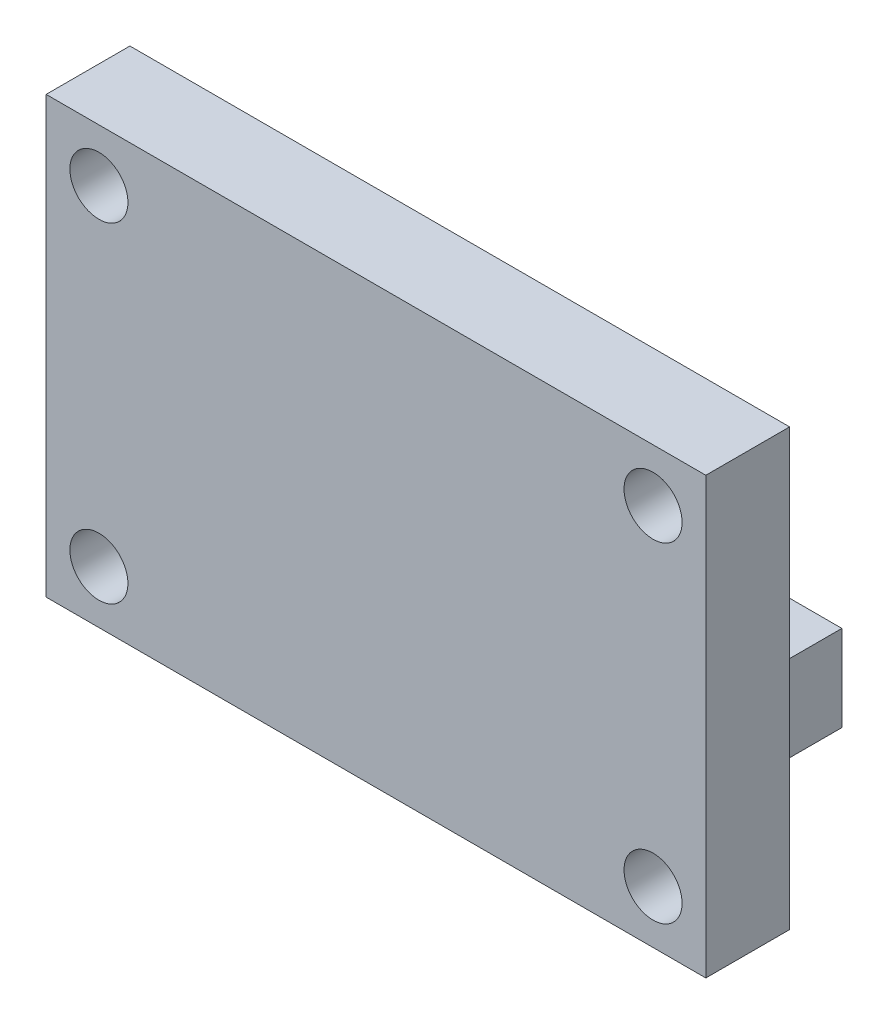
SolidWorks part; units mm, degrees
ref_plane "Front Plane" through (0, 0, 0) normal (0, 0, 1) x (1, 0, 0)
ref_plane "Top Plane" through (0, 0, 0) normal (0, 1, 0) x (1, 0, 0)
ref_plane "Right Plane" through (0, 0, 0) normal (1, 0, 0) x (0, 0, -1)
sketch "Sketch1" plane through (0, 0, 0) normal (0, 0, 1) x (1, 0, 0)
  line L1 (-12.2119, 11.9723) -> (12.7881, 11.9723)
  line L2 (-12.2119, 11.9723) -> (-12.2119, -4.5277)
  line L3 (-12.2119, -4.5277) -> (12.7881, -4.5277)
  line L4 (12.7881, 11.9723) -> (12.7881, -4.5277)
  circle A0 centre (-10.2119, 9.9723) radius 1.1
  circle A1 centre (-10.2119, -2.5277) radius 1.1
  circle A2 centre (10.7881, 9.9723) radius 1.1
  circle A3 centre (10.7881, -2.5277) radius 1.1
  point P13 (0, 0)
  point P14 (0, 0)
  point P15 (0, 0)
  point P16 (0, 0)
  dimension "D3" = 2
  dimension "D1" = 2
  dimension "D2" = 25
  dimension "D4" = 2
  dimension "D5" = 2
  dimension "D6" = 14.5
extrude "Boss-Extrude3" add sketch "Sketch1" against normal blind 3.175
sketch "Sketch4" plane through (0, 0, -3.175) normal (0, 0, -1) x (-1, 0, 0)
  line L5 (12.2119, -4.5277) -> (-12.7881, -4.5277) construction
  line L10 (-7.1488, -4.5277) -> (6.8639, -4.5277)
  line L11 (-7.1488, -4.5277) -> (-7.1488, -1.2708)
  line L12 (-7.1488, -1.2708) -> (6.8639, -1.2708)
  line L13 (6.8639, -4.5277) -> (6.8639, -1.2708)
extrude "Boss-Extrude4" add sketch "Sketch4" along normal blind 7.62
sketch "Sketch8" plane through (0, 0, 0) normal (1, 0, 0) x (0, 0, -1)
  line L0 (3.175, 6.0218) -> (8.7485, -1.0269)
  line L1 (3.175, -4.5277) -> (3.175, 11.9723) construction
rib "Rib13" sketch "Sketch8" sketch "Sketch8" thickness 2.54 extrusion direction parallel to sketch draft on no parameters "D1"=2.54
sketch "Sketch11" plane through (0, -1.2708, 0) normal (0, 1, 0) x (1, 0, 0)
  line L0 (-6.8639, 10.795) -> (7.1488, 10.795) construction
  line L1 (7.1488, 10.795) -> (7.1488, 3.175) construction
  line L2 (-6.8639, 10.795) -> (-6.8639, 3.175) construction
  circle A0 centre (-4.8639, 8.795) radius 1.1
  circle A1 centre (5.1488, 8.795) radius 1.1
  point P4 (0, 0)
  dimension "D1" = 2
  dimension "D2" = 2
  dimension "D3" = 2
extrude "Cut-Extrude3" cut sketch "Sketch11" against normal through all
